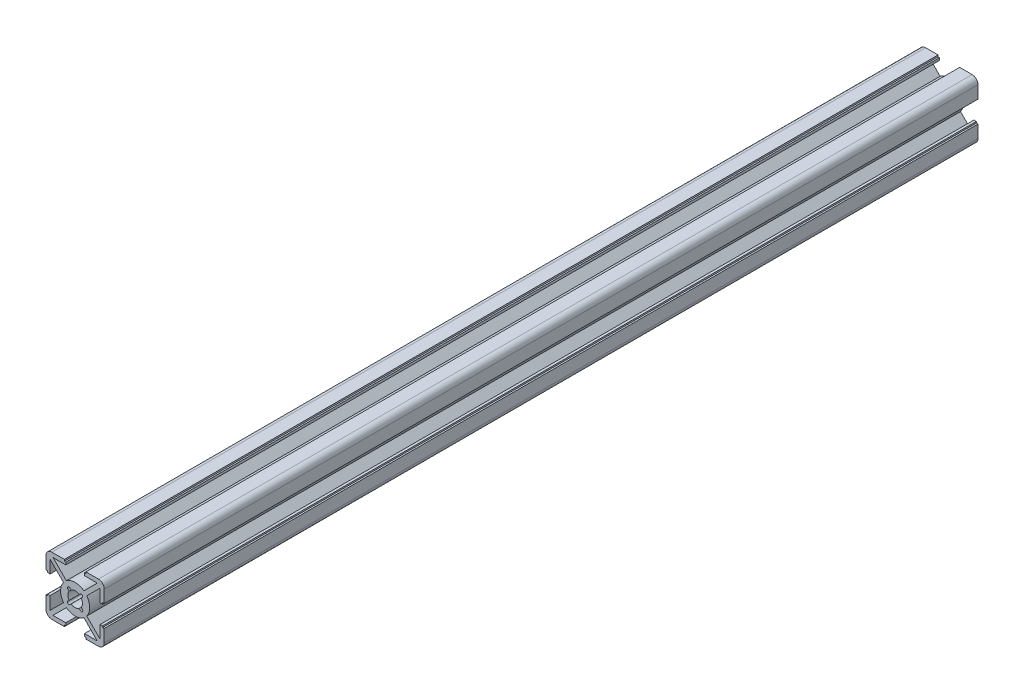
SolidWorks part; units mm, degrees
ref_plane "Ön Düzlem" through (0, 0, 0) normal (0, 0, 1) x (1, 0, 0)
ref_plane "Üst Düzlem" through (0, 0, 0) normal (0, 1, 0) x (1, 0, 0)
ref_plane "Sağ Düzlem" through (0, 0, 0) normal (1, 0, 0) x (0, 0, -1)
sketch "Çizim1" plane through (0, 0, 0) normal (0, 0, 1) x (1, 0, 0)
  line L0 (0, 13.544) -> (0, -12.4346) construction
  line L1 (0, 0) -> (-12.8733, -11.663) construction
  line L2 (15.4428, 0) -> (-17.1022, 0) construction
  line L3 (0, 0) -> (11.9441, 11.9441) construction
  line L4 (2.1213, 2.1213) -> (2.4749, 1.7678) construction
  line L5 (2.4749, 1.7678) -> (1.7678, 2.4749) construction
  line L6 (2.4749, 1.7678) -> (2.0856, 1.3785)
  line L7 (8.6, 7.6101) -> (8.6, 3.2)
  line L8 (1.3785, 2.0856) -> (1.7678, 2.4749)
  line L9 (8, 10) -> (3.7, 10)
  line L10 (3.7, 10) -> (3.7, 9.44)
  line L11 (3.7, 9.44) -> (3.2, 9.44)
  line L12 (3.2, 9.44) -> (3.2, 8.6)
  line L13 (3.0057, 3.9957) -> (7.6101, 8.6)
  line L14 (7.6101, 8.6) -> (3.2, 8.6)
  line L15 (9.44, 3.2) -> (8.6, 3.2)
  line L16 (9.44, 3.7) -> (9.44, 3.2)
  line L17 (10, 3.7) -> (9.44, 3.7)
  line L18 (10, 8) -> (10, 3.7)
  line L19 (8.6, 7.6101) -> (3.9957, 3.0057)
  line L20 (1.3785, -2.0856) -> (1.7678, -2.4749)
  line L21 (2.4749, -1.7678) -> (2.0856, -1.3785)
  line L22 (3.0057, -3.9957) -> (7.6101, -8.6)
  line L23 (3.2, -9.44) -> (3.2, -8.6)
  line L24 (3.7, -9.44) -> (3.2, -9.44)
  line L25 (3.7, -10) -> (3.7, -9.44)
  line L26 (7.6101, -8.6) -> (3.2, -8.6)
  line L27 (8, -10) -> (3.7, -10)
  line L28 (8.6, -7.6101) -> (3.9957, -3.0057)
  line L29 (8.6, -7.6101) -> (8.6, -3.2)
  line L30 (9.44, -3.2) -> (8.6, -3.2)
  line L31 (9.44, -3.7) -> (9.44, -3.2)
  line L32 (10, -3.7) -> (9.44, -3.7)
  line L33 (10, -8) -> (10, -3.7)
  line L34 (-1.3785, 2.0856) -> (-1.7678, 2.4749)
  line L35 (-2.4749, 1.7678) -> (-1.7678, 2.4749) construction
  line L36 (-2.1213, 2.1213) -> (-2.4749, 1.7678) construction
  line L37 (-10, -8) -> (-10, -3.7)
  line L38 (-10, -3.7) -> (-9.44, -3.7)
  line L39 (-9.44, -3.7) -> (-9.44, -3.2)
  line L40 (-9.44, -3.2) -> (-8.6, -3.2)
  line L41 (-8.6, -7.6101) -> (-8.6, -3.2)
  line L42 (-8.6, -7.6101) -> (-3.9957, -3.0057)
  line L43 (-8, -10) -> (-3.7, -10)
  line L44 (-7.6101, -8.6) -> (-3.2, -8.6)
  line L45 (-3.7, -10) -> (-3.7, -9.44)
  line L46 (-3.7, -9.44) -> (-3.2, -9.44)
  line L47 (-3.2, -9.44) -> (-3.2, -8.6)
  line L48 (-3.0057, -3.9957) -> (-7.6101, -8.6)
  line L49 (-2.4749, -1.7678) -> (-2.0856, -1.3785)
  line L50 (-1.3785, -2.0856) -> (-1.7678, -2.4749)
  line L51 (-8.6, 7.6101) -> (-3.9957, 3.0057)
  line L52 (-10, 8) -> (-10, 3.7)
  line L53 (-10, 3.7) -> (-9.44, 3.7)
  line L54 (-9.44, 3.7) -> (-9.44, 3.2)
  line L55 (-9.44, 3.2) -> (-8.6, 3.2)
  line L56 (-7.6101, 8.6) -> (-3.2, 8.6)
  line L57 (-3.0057, 3.9957) -> (-7.6101, 8.6)
  line L58 (-3.2, 9.44) -> (-3.2, 8.6)
  line L59 (-3.7, 9.44) -> (-3.2, 9.44)
  line L60 (-3.7, 10) -> (-3.7, 9.44)
  line L61 (-8, 10) -> (-3.7, 10)
  line L62 (-8.6, 7.6101) -> (-8.6, 3.2)
  line L63 (-2.4749, 1.7678) -> (-2.0856, 1.3785)
  arc A0 (1.3785, 2.0856) -> (-1.3785, 2.0856) centre (0, 0) ccw
  arc A1 (2.4749, 1.7678) -> (1.7678, 2.4749) centre (2.1213, 2.1213) ccw
  arc A2 (3.0057, 3.9957) -> (-3.0057, 3.9957) centre (0, 0) ccw
  arc A3 (3.9957, -3.0057) -> (3.9957, 3.0057) centre (0, 0) ccw
  arc A4 (2.0856, -1.3785) -> (2.0856, 1.3785) centre (0, 0) ccw
  arc A5 (1.3785, -2.0856) -> (-1.3785, -2.0856) centre (0, 0) cw
  arc A6 (2.4749, -1.7678) -> (1.7678, -2.4749) centre (2.1213, -2.1213) cw
  arc A7 (3.0057, -3.9957) -> (-3.0057, -3.9957) centre (0, 0) cw
  arc A8 (-2.4749, -1.7678) -> (-1.7678, -2.4749) centre (-2.1213, -2.1213) ccw
  arc A9 (-2.0856, -1.3785) -> (-2.0856, 1.3785) centre (0, 0) cw
  arc A10 (-3.9957, -3.0057) -> (-3.9957, 3.0057) centre (0, 0) cw
  arc A11 (-2.4749, 1.7678) -> (-1.7678, 2.4749) centre (-2.1213, 2.1213) cw
  arc A12 (-10, -8) -> (-8, -10) centre (-8, -8) ccw
  arc A13 (8, -10) -> (10, -8) centre (8, -8) ccw
  arc A14 (10, 8) -> (8, 10) centre (8, 8) ccw
  arc A15 (-10, 8) -> (-8, 10) centre (-8, 8) cw
  point P82 (-10, -10)
  point P85 (10, -10)
  point P88 (10, 10)
  point P91 (-10, 10)
  dimension "D1" = 5
  dimension "D3" = 1
  dimension "D6" = 10
  dimension "D8" = 2
  dimension "D2" = 45
  dimension "D4" = 0.5
  dimension "D5" = 3.2
  dimension "D7" = 0.7
  dimension "D10" = 1.4
  dimension "D12" = 0.84
extrude "Yükseklik-Ekstrüzyon1" add sketch "Çizim1" along normal blind 300
